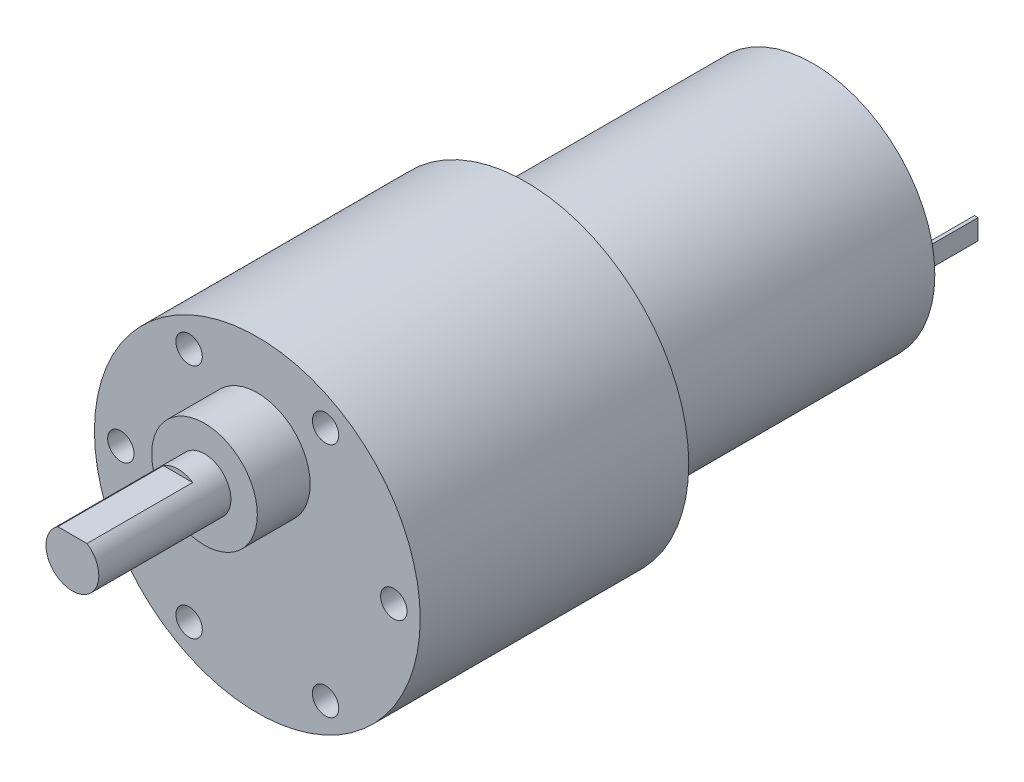
SolidWorks part; units mm, degrees
ref_plane "正面" through (0, 0, 0) normal (0, 0, 1) x (1, 0, 0)
ref_plane "平面" through (0, 0, 0) normal (0, 1, 0) x (1, 0, 0)
ref_plane "右側面" through (0, 0, 0) normal (1, 0, 0) x (0, 0, -1)
sketch "ｽｹｯﾁ1" plane through (0, 0, 0) normal (0, 0, 1) x (1, 0, 0)
  circle A0 centre (0, 0) radius 13.85
  dimension "D1" = 27.7
extrude "ﾎﾞｽ - 押し出し1" add sketch "ｽｹｯﾁ1" along normal blind 32.6
sketch "ｽｹｯﾁ2" plane through (0, 0, 32.6) normal (0, 0, 1) x (1, 0, 0)
  circle A0 centre (0, 0) radius 18.5
  dimension "D1" = 37
extrude "ﾎﾞｽ - 押し出し2" add sketch "ｽｹｯﾁ2" along normal blind 30.5
sketch "ｽｹｯﾁ3" plane through (0, 0, 63.1) normal (0, 0, 1) x (1, 0, 0)
  circle A0 centre (0, 7) radius 6
  point P2 (0, 0)
  dimension "D1" = 12
  dimension "D2" = 7
extrude "ﾎﾞｽ - 押し出し3" add sketch "ｽｹｯﾁ3" along normal blind 6
sketch "ｽｹｯﾁ4" plane through (0, 0, 69.1) normal (0, 0, 1) x (1, 0, 0)
  circle A0 centre (0, 7) radius 3
  dimension "D1" = 6
extrude "ﾎﾞｽ - 押し出し4" add sketch "ｽｹｯﾁ4" along normal blind 15
sketch "ｽｹｯﾁ5" plane through (0, 0, 84.1) normal (0, 0, 1) x (1, 0, 0)
  line L0 (-1.6583, 9.5) -> (1.6583, 9.5)
  arc A0 (-1.6583, 9.5) -> (1.6583, 9.5) centre (0, 7) cw
  circle A1 centre (0, 7) radius 3 construction
  dimension "D1" = 2.5
extrude "ｶｯﾄ - 押し出し1" cut sketch "ｽｹｯﾁ5" against normal blind 12
sketch "ｽｹｯﾁ6" plane through (0, 0, 63.1) normal (0, 0, 1) x (1, 0, 0)
  circle A0 centre (-15.5, 0) radius 1.5
  circle A1 centre (0, 0) radius 15.5 construction
  circle A2 centre (-7.75, 13.4234) radius 1.5
  circle A3 centre (7.75, 13.4234) radius 1.5
  circle A4 centre (15.5, 0) radius 1.5
  circle A5 centre (7.75, -13.4234) radius 1.5
  circle A6 centre (-7.75, -13.4234) radius 1.5
  point P5 (-4.0835, -14.5324)
  point P6 (-7.9768, 15.1581)
  point P17 (0, 0)
  point P18 (0, 0)
  point P19 (0, 0)
  point P20 (0, 0)
  point P21 (0, 0)
  point P22 (0, 0)
  dimension "D1" = 31
  dimension "D2" = 3
  dimension "D3" = 6
extrude "ｶｯﾄ - 押し出し2" cut sketch "ｽｹｯﾁ6" against normal blind 3.5
sketch "ｽｹｯﾁ7" plane through (0, 0, 0) normal (0, 0, -1) x (-1, 0, 0)
  circle A0 centre (0, 0) radius 5
  dimension "D1" = 10
extrude "ﾎﾞｽ - 押し出し5" add sketch "ｽｹｯﾁ7" along normal blind 2.6
sketch "ｽｹｯﾁ8" plane through (0, 0, -2.6) normal (0, 0, -1) x (-1, 0, 0)
  circle A0 centre (0, 0) radius 1.15
  dimension "D1" = 2.3
extrude "ﾎﾞｽ - 押し出し6" add sketch "ｽｹｯﾁ8" along normal blind 8.5 from surface at -2.6 starting at face at (-5, 0, 0)
sketch "ｽｹｯﾁ9" plane through (0, 0, 0) normal (0, 0, -1) x (-1, 0, 0)
  line L0 (0, 22.7928) -> (0, -25.5728) construction
  line L1 (11.85, -1.15) -> (11.45, -1.15)
  line L2 (-11.85, 1.15) -> (-11.45, 1.15)
  line L3 (-11.85, 1.15) -> (-11.85, -1.15)
  line L4 (-11.85, -1.15) -> (-11.45, -1.15)
  line L5 (-11.45, 1.15) -> (-11.45, -1.15)
  line L6 (-11.85, 1.15) -> (-11.45, -1.15) construction
  line L7 (-11.85, -1.15) -> (-11.45, 1.15) construction
  line L8 (11.45, 1.15) -> (11.45, -1.15)
  line L9 (11.85, 1.15) -> (11.45, 1.15)
  line L10 (11.85, 1.15) -> (11.85, -1.15)
  point P7 (-11.65, 0)
  point P8 (0, 0)
  dimension "D1" = 0.4
  dimension "D2" = 2.3
  dimension "D3" = 22.9
extrude "ﾎﾞｽ - 押し出し7" add sketch "ｽｹｯﾁ9" along normal blind 6.9
